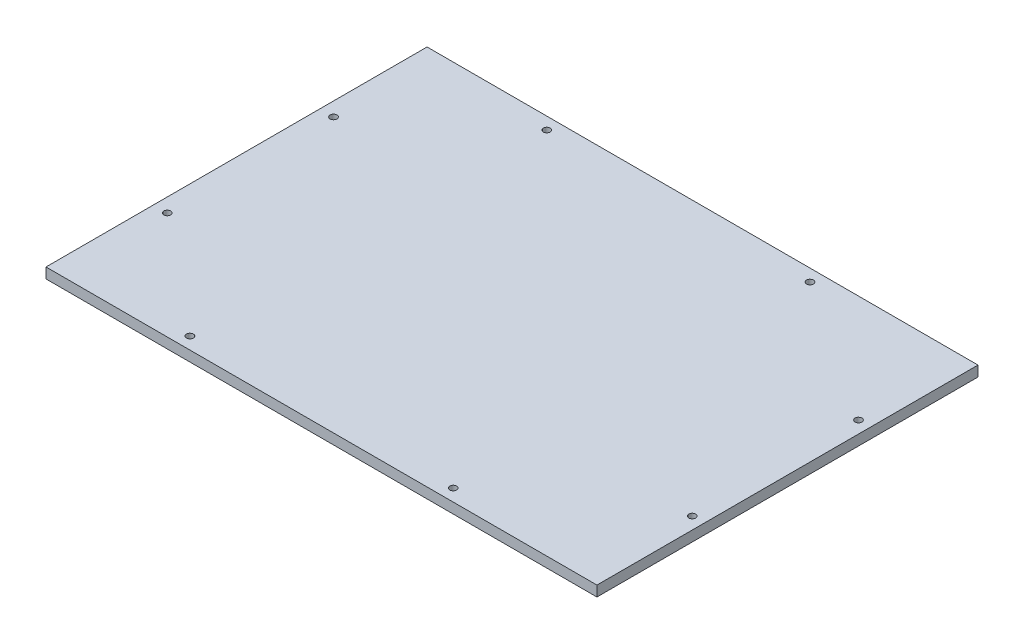
SolidWorks part; units mm, degrees
ref_plane "Front Plane" through (0, 0, 0) normal (0, 0, 1) x (1, 0, 0)
ref_plane "Top Plane" through (0, 0, 0) normal (0, 1, 0) x (1, 0, 0)
ref_plane "Right Plane" through (0, 0, 0) normal (1, 0, 0) x (0, 0, -1)
sketch "Sketch1" plane through (0, 0, 0) normal (0, 1, 0) x (1, 0, 0)
  line L1 (0, 0) -> (-504.952, 0)
  line L2 (0, 0) -> (0, -349.25)
  line L3 (0, -349.25) -> (-504.952, -349.25)
  line L4 (-504.952, 0) -> (-504.952, -349.25)
  dimension "D1" = 504.952
  dimension "D2" = 349.25
extrude "Boss-Extrude1" add sketch "Sketch1" along normal blind 9.525
sketch "Sketch2" plane through (0, 9.525, 0) normal (0, 1, 0) x (1, 0, 0)
  circle A0 centre (-384.175, -11.1125) radius 3.175
  circle A1 centre (-142.875, -11.1125) radius 3.175
  circle A2 centre (-11.1125, -98.425) radius 3.175
  circle A3 centre (-11.1125, -250.825) radius 3.175
  circle A4 centre (-142.875, -338.1375) radius 3.175
  circle A5 centre (-384.175, -338.1375) radius 3.175
  circle A6 centre (-492.252, -250.825) radius 3.175
  circle A7 centre (-492.252, -98.425) radius 3.175
extrude "Cut-Extrude1" cut sketch "Sketch2" against normal up to surface (12.7 mm away)
